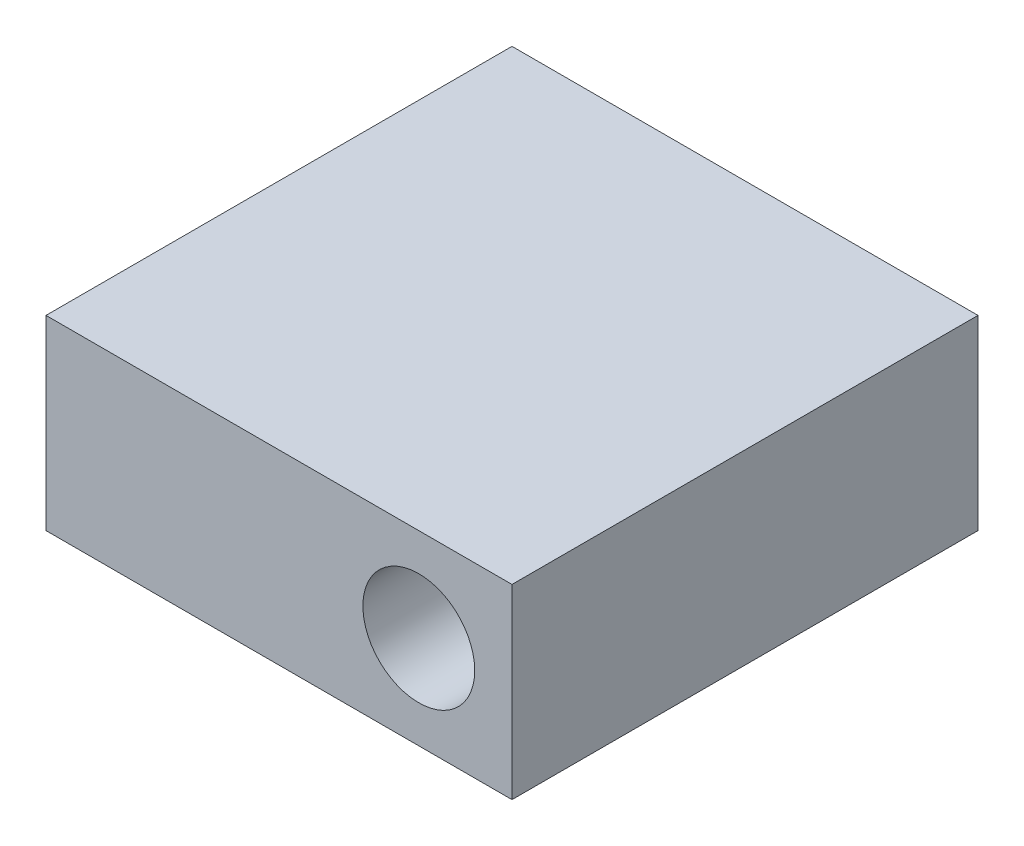
SolidWorks part; units mm, degrees
ref_plane "Front Plane" through (0, 0, 0) normal (0, 0, 1) x (1, 0, 0)
ref_plane "Top Plane" through (0, 0, 0) normal (0, 1, 0) x (1, 0, 0)
ref_plane "Right Plane" through (0, 0, 0) normal (1, 0, 0) x (0, 0, -1)
sketch "Sketch1" plane through (0, 0, 0) normal (0, 1, 0) x (1, 0, 0)
  line L1 (-12.5, -12.5) -> (12.5, -12.5)
  line L2 (-12.5, -12.5) -> (-12.5, 12.5)
  line L3 (-12.5, 12.5) -> (12.5, 12.5)
  line L4 (12.5, -12.5) -> (12.5, 12.5)
  line L5 (-12.5, -12.5) -> (12.5, 12.5) construction
  line L6 (-12.5, 12.5) -> (12.5, -12.5) construction
  point P0 (0, 0)
  dimension "D1" = 25
  dimension "D2" = 25
extrude "Boss-Extrude1" add sketch "Sketch1" along normal blind 10
sketch "Sketch2" plane through (0, 0, 12.5) normal (0, 0, 1) x (1, 0, 0)
  line L0 (12.5, 5) -> (7.5, 5) construction
  line L1 (12.5, 10) -> (12.5, 0) construction
  circle A0 centre (7.5, 5) radius 3
  dimension "D2" = 6
  dimension "D1" = 5
extrude "Cut-Extrude1" cut sketch "Sketch2" against normal blind 10
